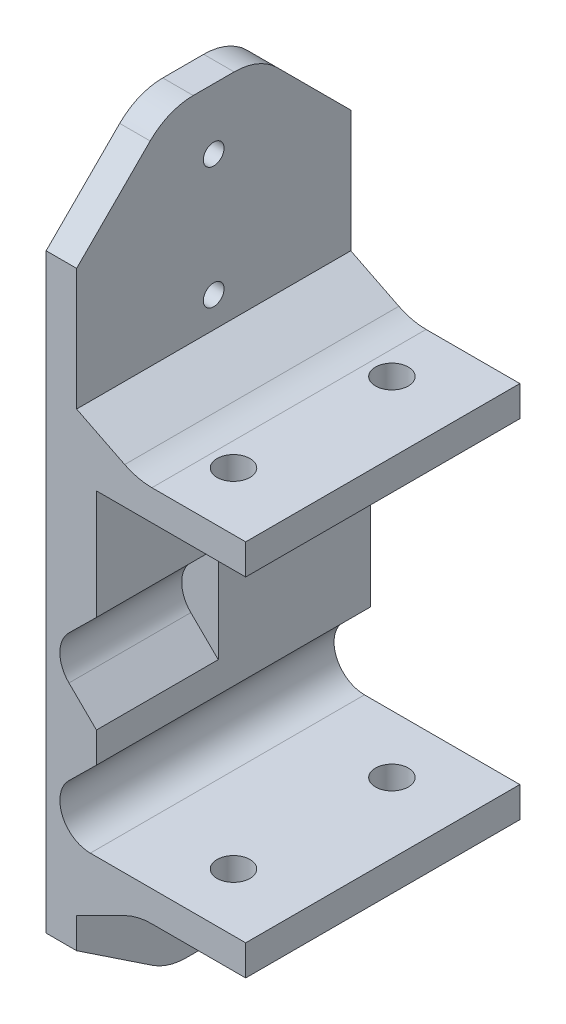
SolidWorks part; units mm, degrees
ref_plane "Front Plane" through (0, 0, 0) normal (0, 0, 1) x (1, 0, 0)
ref_plane "Top Plane" through (0, 0, 0) normal (0, 1, 0) x (1, 0, 0)
ref_plane "Right Plane" through (0, 0, 0) normal (1, 0, 0) x (0, 0, -1)
sketch "Sketch1" plane through (0, 0, 0) normal (0, 0, 1) x (1, 0, 0)
  line L0 (0, 0) -> (0, -5)
  line L1 (0, -5) -> (-27.75, -5)
  line L2 (-27.75, -5) -> (-27.75, -25)
  line L3 (-27.75, -25) -> (-32.75, -25)
  line L4 (-32.75, -25) -> (-32.75, 97)
  line L5 (-32.75, 97) -> (-27.75, 97)
  line L6 (-27.75, 97) -> (-27.75, 57)
  line L7 (-27.75, 57) -> (0, 57)
  line L8 (0, 57) -> (0, 52)
  line L9 (0, 52) -> (-24.5, 52)
  line L10 (-24.5, 52) -> (-24.5, 0)
  line L11 (-24.5, 0) -> (0, 0)
  dimension "D1" = 24.5
  dimension "D2" = 8.25
  dimension "D3" = 52
  dimension "D4" = 5
  dimension "D5" = 5
  dimension "D6" = 20
  dimension "D7" = 40
extrude "Boss-Extrude1" add sketch "Sketch1" along normal blind 45
sketch "Sketch3" plane through (-27.75, 0, 0) normal (1, 0, 0) x (0, 0, -1)
  line L0 (-45, 57) -> (-45, 82)
  line L1 (-45, 57) -> (-45, 97) construction
  line L2 (-45, 82) -> (-30, 97)
  line L3 (-45, 97) -> (0, 97) construction
  line L4 (-30, 97) -> (-15, 97)
  line L5 (-15, 97) -> (0, 82)
  line L6 (0, 57) -> (0, 97) construction
  line L7 (0, 82) -> (0, 57)
  line L8 (0, 57) -> (-45, 57)
  line L9 (-45, -5) -> (-45, -15)
  line L10 (-45, -25) -> (-45, -5) construction
  line L11 (-45, -15) -> (-30, -25)
  line L12 (-30, -25) -> (-15, -25)
  line L13 (-45, -25) -> (0, -25) construction
  line L14 (-15, -25) -> (0, -15)
  line L15 (0, -25) -> (0, -5) construction
  line L16 (0, -15) -> (0, -5)
  line L17 (0, -5) -> (-45, -5)
  line L19 (-45, 57) -> (0, 57)
  line L20 (-45, 57) -> (-45, 97)
  line L21 (-45, 97) -> (0, 97)
  line L22 (0, 57) -> (0, 97)
  line L23 (-45, -25) -> (0, -25)
  line L24 (-45, -25) -> (-45, -5)
  line L25 (-45, -5) -> (0, -5)
  line L26 (0, -25) -> (0, -5)
  circle A0 centre (-22.5, 67) radius 1.7
  circle A1 centre (-22.5, 87) radius 1.7
  circle A2 centre (-22.5, -15) radius 1.7
  point P41 (-22.5, -25)
  line M13 (0, 57) -> (0, 97)
  line M14 (0, 97) -> (-45, 97)
  line M15 (-45, 97) -> (-45, 57)
  dimension "D3" = 3.4
  dimension "D1" = 15
  dimension "D2" = 15
  dimension "D4" = 10
  dimension "D5" = 20
  dimension "D6" = 10
  dimension "D7" = 135
extrude "Cut-Extrude1" cut sketch "Sketch3" against normal through all contours L2 M15 M14 | L5 M14 M13 | L24 L23 L11 | L23 L26 L14 | A2 | A1 | A0
chamfer "Chamfer1" distance 5 distance2 10 1 edges at (-27.75, -5, 22.5)
chamfer "Chamfer2" distance 10 distance2 5 1 edges at (-27.75, 57, 22.5)
fillet "Fillet1" radius 10 6 edges at (-17.75, -5, 22.5) (-17.75, 57, 22.5) (-30.25, -25, 30) (-30.25, -25, 15) (-30.25, 97, 30) (-30.25, 97, 15)
sketch "Sketch5" plane through (0, 0, 0) normal (0, 1, 0) x (1, 0, 0)
  line L0 (-24.5, -45) -> (-24.5, 0) construction
  line L3 (0, -22.5) -> (-24.5, -22.5) construction
  line L4 (0, -45) -> (0, 0) construction
  line L5 (-11.5, -35.5) -> (-11.5, -9.5) construction
  circle A0 centre (-11.5, -9.5) radius 2.7
  circle A1 centre (-11.5, -35.5) radius 2.7
  point P10 (-11.5, -22.5)
  dimension "D2" = 5.4
  dimension "D1" = 13
  dimension "D3" = 26
extrude "Cut-Extrude2" cut sketch "Sketch5" against normal through all both and the other way through all
sketch "Sketch6" plane through (0, 0, 45) normal (0, 0, 1) x (1, 0, 0)
  line L0 (-24.5, 0) -> (-32.75, 0) construction
  line L1 (-32.75, 82) -> (-32.75, -15) construction
  line L2 (-24.5, 10) -> (-24.5, 13)
  line L3 (-24.5, 5) -> (-30.5, 5) construction
  line L4 (-24.5, 13) -> (-29.0074, 8.5634)
  line L10 (-24.5, 0) -> (-24.5, 52) construction
  line L12 (-25.5, 10) -> (-24.5, 10)
  line L13 (-25.5, 10) -> (-25.5, 0)
  line L14 (-25.5, 0) -> (-24.5, 0)
  line L15 (-24.5, 10) -> (-24.5, 0)
  circle A2 centre (-25.5, 5) radius 5
  dimension "D1" = 3
  dimension "D3" = 10
  dimension "D4" = 6
extrude "Cut-Extrude3" cut sketch "Sketch6" against normal through all
sketch "Sketch7" plane through (0, 0, 45) normal (0, 0, 1) x (1, 0, 0)
  line L0 (-24.5, 21) -> (-24.5, 18)
  line L4 (-25.5, 26) -> (-25.5, 21)
  line L5 (-24.5, 13) -> (-24.5, 52) construction
  line L6 (-24.5, 26) -> (-30.5, 26) construction
  line L7 (-25.5, 31) -> (-24.5, 31)
  line L8 (-25.5, 31) -> (-25.5, 21)
  line L9 (-25.5, 21) -> (-24.5, 21)
  line L10 (-24.5, 31) -> (-24.5, 21)
  line L11 (0, 0) -> (-25.5, 0) construction
  line L12 (-24.5, 13) -> (-24.5, 52) construction
  line L13 (-24.5, 18) -> (-29.0074, 22.4366)
  line L14 (-24.5, 31) -> (-24.5, 34)
  line L15 (-24.5, 34) -> (-29.0074, 29.5634)
  circle A0 centre (-25.5, 26) radius 5
  line M21 (-24.5, 13) -> (-24.5, 52)
  dimension "D1" = 6
  dimension "D2" = 21
  dimension "D3" = 3
  dimension "D4" = 3
extrude "Cut-Extrude4" cut sketch "Sketch7" against normal blind 20 contours A0 L8 L4 | A0 L9 M21 | A0 L10 L7 | L8 A0 L4 | L6 A0 L8 M21 | A0 L13 L9 M21 | A0 L7 L15 M21 | A0 L7 M21
